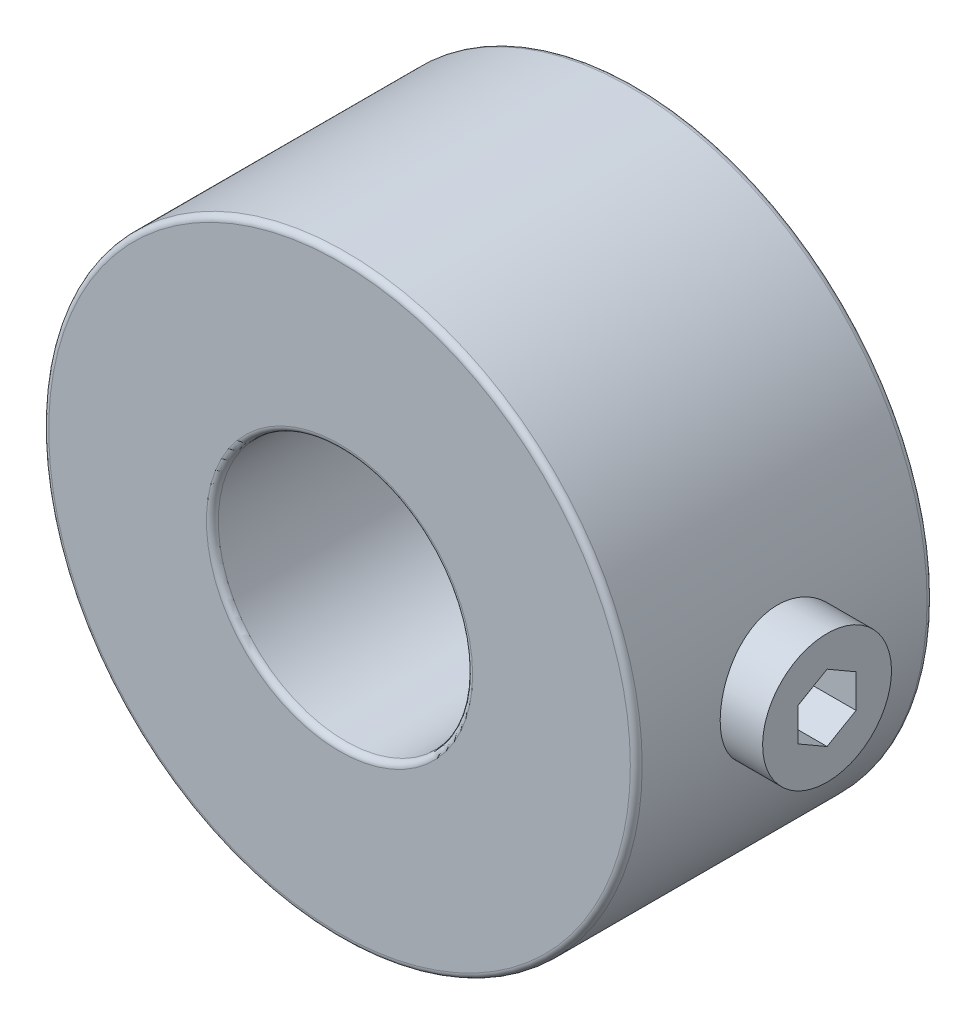
SolidWorks part; units mm, degrees
material "Nylon 6/10"
ref_plane "Front Plane" through (0, 0, 0) normal (0, 0, 1) x (1, 0, 0)
ref_plane "Top Plane" through (0, 0, 0) normal (0, 1, 0) x (1, 0, 0)
ref_plane "Right Plane" through (0, 0, 0) normal (1, 0, 0) x (0, 0, -1)
sketch "Sketch1" plane through (0, 0, 0) normal (0, 0, 1) x (1, 0, 0)
  circle A0 centre (0, 0) radius 11.1125
  circle A1 centre (0, 0) radius 4.7625
  point P4 (11.1125, 0)
  dimension "Bore Dia" = 9.525
  dimension "OD" = 22.225
extrude "Extrude1" add sketch "Sketch1" along normal blind 11.1125
ref_plane "Plane1" through (11.1125, 0, 0) normal (1, 0, 0) x (0, 0, -1)
sketch "Sketch2" plane through (11.1125, 0, 0) normal (1, 0, 0) x (0, 0, -1)
  line L0 (0, 0) -> (-11.1125, 0) construction
  line L1 (-11.1125, 11.1125) -> (-11.1125, -11.1125) construction
  circle A0 centre (-5.5562, 0) radius 2.413
  dimension "Set Screw Dia" = 4.826
extrude "Cut-Extrude1" cut sketch "Sketch2" against normal up to surface (11.1125 mm away) up to plane "Right Plane"
ref_plane "Plane2" through (0, 0, 5.5562) normal (0, 0, 1) x (1, 0, 0)
sketch "Sketch3" plane through (0, 0, 5.5562) normal (0, 0, 1) x (1, 0, 0)
  line L1 (6.35, 0) -> (12.7, 0)
  line L2 (6.35, 0) -> (6.35, 2.413)
  line L3 (6.35, 2.413) -> (12.7, 2.413)
  line L4 (12.7, 0) -> (12.7, 2.413)
  line L5 (6.35, 0) -> (0, 0) construction
  dimension "D1" = 6.35
  dimension "D2" = 1.5875
  dimension "D3" = 4.826
revolve "Revolve1" add sketch "Sketch3" angle 360 about L1
sketch "Sketch4" plane through (12.7, 0, 0) normal (1, 0, 0) x (0, 0, -1)
  line L1 (-5.5562, 1.2538) -> (-6.6421, 0.6269)
  line L2 (-6.6421, 0.6269) -> (-6.6421, -0.6269)
  line L3 (-6.6421, -0.6269) -> (-5.5562, -1.2538)
  line L4 (-5.5562, -1.2538) -> (-4.4704, -0.6269)
  line L5 (-4.4704, -0.6269) -> (-4.4704, 0.6269)
  line L6 (-4.4704, 0.6269) -> (-5.5562, 1.2538)
  circle A0 centre (-5.5562, 0) radius 1.0858 construction
  dimension "D1" = 2.1717
extrude "Cut-Extrude2" cut sketch "Sketch4" against normal up to vertex (1.5875 mm away) up to point (11.1125, 0, 5.5562)
fillet "Fillet1" radius 0.2223 4 edges at (4.7625, 0, 0) (4.7625, 0, 11.1125) (11.1125, 0, 0) (11.1125, 0, 11.1125)
equation "\"D1@Sketch3\" = (\"OD@Sketch1\"-\"Bore Dia@Sketch1\")/2"
equation "\"D2@Sketch3\" = \"D1@Sketch3\"/4"
equation "\"D1@Sketch4\" = \"Set Screw Dia@Sketch2\"*.45"
equation "\"D3@Sketch3\" = \"Set Screw Dia@Sketch2\""
equation "\"D1@Fillet1\" = \"OD@Sketch1\"*.01"
